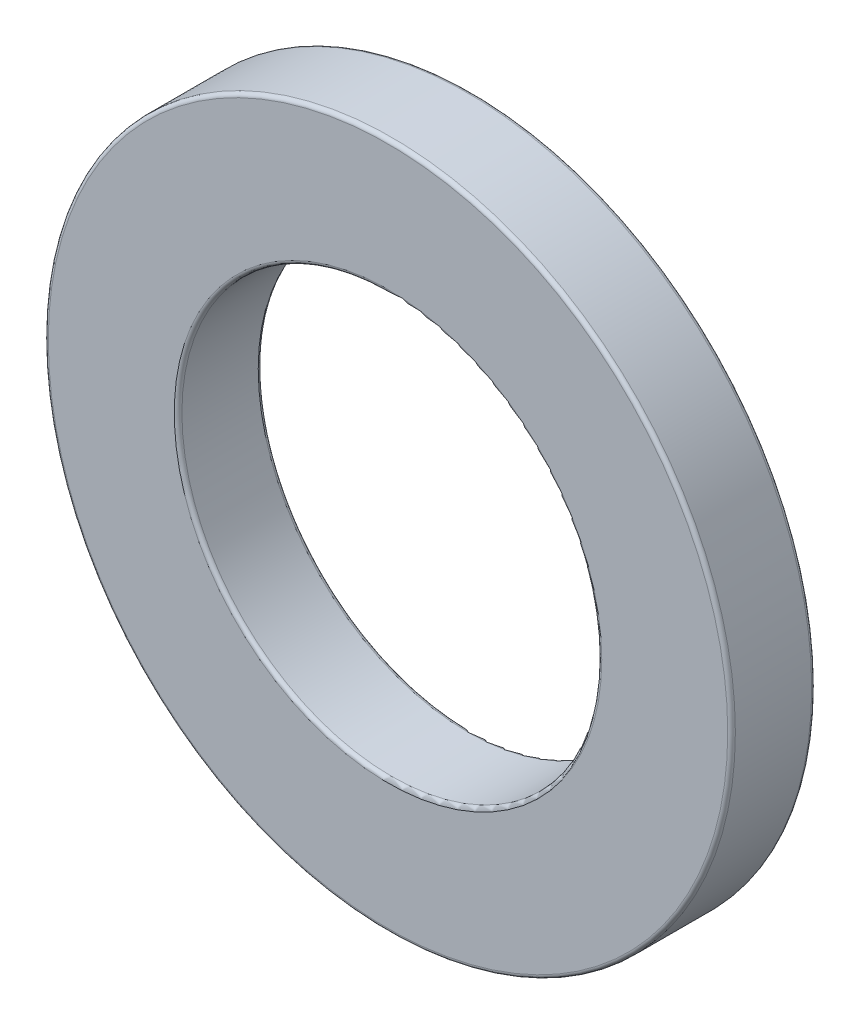
SolidWorks part; units mm, degrees
ref_plane "前视基准面" through (0, 0, 0) normal (0, 0, 1) x (1, 0, 0)
ref_plane "上视基准面" through (0, 0, 0) normal (0, 1, 0) x (1, 0, 0)
ref_plane "右视基准面" through (0, 0, 0) normal (1, 0, 0) x (0, 0, -1)
sketch "草图1" plane through (0, 0, 0) normal (0, 0, 1) x (1, 0, 0)
  circle A0 centre (0, 0) radius 45
  circle A1 centre (0, 0) radius 27.5
extrude "拉伸1" add sketch "草图1" along normal blind 11
fillet "圆角1" radius 0.5 4 edges at (45, 0, 0) (45, 0, 11) (27.5, 0, 0) (27.5, 0, 11)
